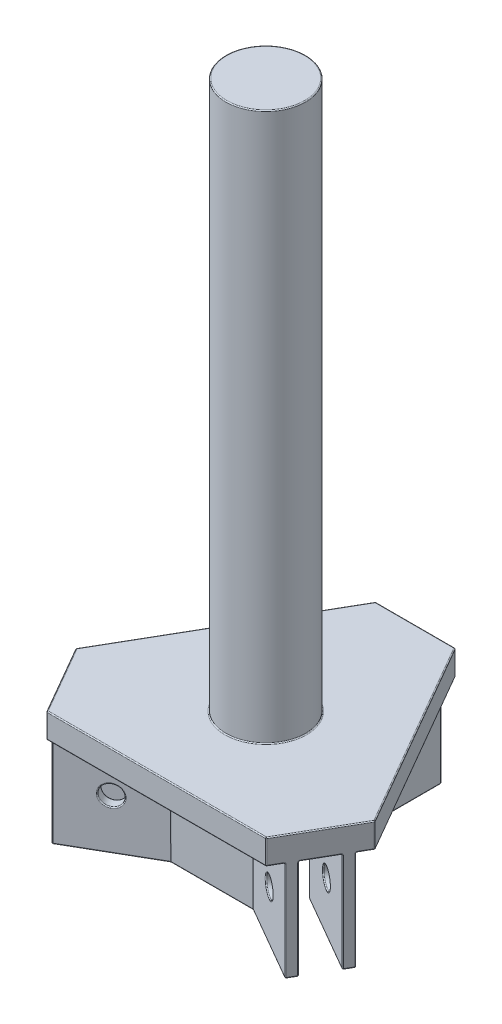
SolidWorks part; units mm, degrees
ref_plane "Front Plane" through (0, 0, 0) normal (0, 0, 1) x (1, 0, 0)
ref_plane "Top Plane" through (0, 0, 0) normal (0, 1, 0) x (1, 0, 0)
ref_plane "Right Plane" through (0, 0, 0) normal (1, 0, 0) x (0, 0, -1)
sketch "Sketch1" plane through (0, 0, 0) normal (0, 1, 0) x (1, 0, 0)
  line L0 (-13, -7.5056) -> (0, 0) construction
  line L1 (0, 0) -> (0, 15.0111) construction
  line L2 (0, 0) -> (13, -7.5056) construction
  line L3 (-4, 15.0111) -> (4, 15.0111)
  line L4 (-15, -4.0415) -> (-11, -10.9697)
  line L5 (15, -4.0415) -> (11, -10.9697)
  line L6 (-4, 15.0111) -> (-15, -4.0415)
  line L7 (-11, -10.9697) -> (11, -10.9697)
  line L8 (15, -4.0415) -> (4, 15.0111)
  point P7 (0, 15.0111)
  point P10 (-13, -7.5056)
  point P13 (13, -7.5056)
  dimension "D1" = 120
  dimension "D2" = 120
  dimension "D3" = 120
  dimension "D4" = 8
  dimension "D5" = 22
extrude "Boss-Extrude1" add sketch "Sketch1" along normal blind 2.5
sketch "Sketch2" plane through (0, 0, 0) normal (0, -1, 0) x (1, 0, 0)
  line L0 (0, 0) -> (-13, 7.5056) construction
  line L1 (-15, 4.0415) -> (-11, 10.9697) construction
  line L2 (13, 7.5056) -> (0, 0) construction
  line L3 (11, 10.9697) -> (15, 4.0415) construction
  line L4 (0, 0) -> (0, -15.0111) construction
  line L5 (4, -15.0111) -> (-4, -15.0111) construction
  line L6 (-12.2, 8.8912) -> (-4.4058, 4.3912)
  line L7 (-4.4058, 4.3912) -> (4.4058, 4.3912)
  line L8 (4.4058, 4.3912) -> (12.2, 8.8912)
  line L9 (-11.7, 9.7572) -> (-4.1378, 5.3912)
  line L10 (-4.1378, 5.3912) -> (4.1378, 5.3912)
  line L11 (4.1378, 5.3912) -> (11.7, 9.7572)
  line L12 (-11.7, 9.7572) -> (-12.2, 8.8912)
  line L13 (11.7, 9.7572) -> (12.2, 8.8912)
  line L14 (2.6, -15.0111) -> (1.6, -15.0111)
  line L15 (1.6, -6.0111) -> (1.6, -15.0111)
  line L16 (6.0058, 1.6199) -> (1.6, -6.0111)
  line L17 (13.8, 6.1199) -> (6.0058, 1.6199)
  line L18 (14.3, 5.2539) -> (13.8, 6.1199)
  line L19 (14.3, 5.2539) -> (6.7378, 0.8879)
  line L20 (6.7378, 0.8879) -> (2.6, -6.2791)
  line L21 (2.6, -6.2791) -> (2.6, -15.0111)
  line L22 (-14.3, 5.2539) -> (-13.8, 6.1199)
  line L23 (-6.0058, 1.6199) -> (-13.8, 6.1199)
  line L24 (-1.6, -6.0111) -> (-6.0058, 1.6199)
  line L25 (-1.6, -15.0111) -> (-1.6, -6.0111)
  line L26 (-2.6, -15.0111) -> (-1.6, -15.0111)
  line L27 (-2.6, -15.0111) -> (-2.6, -6.2791)
  line L28 (-2.6, -6.2791) -> (-6.7378, 0.8879)
  line L29 (-6.7378, 0.8879) -> (-14.3, 5.2539)
  circle A0 centre (0, 0) radius 4 construction
  point P14 (0, 4.3912)
  point P40 (0, 0)
  dimension "D1" = 8
  dimension "D2" = 9
  dimension "D3" = 9
  dimension "D4" = 1.6
  dimension "D5" = 1
  dimension "D6" = 3
extrude "Boss-Extrude2" add sketch "Sketch2" along normal blind 10
sketch "Sketch3" plane through (0, 2.5, 0) normal (0, 1, 0) x (1, 0, 0)
  circle A0 centre (0, 0) radius 4 construction
  circle A1 centre (0, 0) radius 4
extrude "Boss-Extrude3" add sketch "Sketch3" along normal blind 55
sketch "Sketch4" plane through (1.3, 0, 2.2517) normal (0.5, 0, 0.866) x (0.866, 0, -0.5)
  line L0 (-6.2791, -5) -> (-15.0111, -5) construction
  line L1 (-6.2791, -10) -> (-6.2791, 0) construction
  line L2 (-15.0111, -10) -> (-15.0111, 0) construction
  circle A0 centre (-10.6451, -5) radius 1
  dimension "D1" = 2
extrude "Cut-Extrude1" cut sketch "Sketch4" against normal through all
pattern_circular "CirPattern1" count 3 over 360 about axis through (0, 57.5, 0) along (0, -1, 0) of "Cut-Extrude1"
fillet "Fillet1" radius 0.1 104 edges at (-7.5529, -5, 6.2082) (-4.4058, -5, 4.3912) (4.4058, -5, 4.3912) (9.2849, -5, 7.2082) (7.0529, -5, 7.0742) (4.1378, -5, 5.3912) (-4.1378, -5, 5.3912) (-7.0529, -5, 7.0742) (-7.9189, -10, 7.5742) (0, -10, 5.3912) (7.9189, -10, 7.5742) (8.3029, -10, 6.6412) (0, -10, 4.3912) (-8.3029, -10, 6.6412) (9.1529, -5, 3.4369) (6.0058, -5, 1.6199) (1.6, -5, -6.0111) (1.6, -5, -11.6451) (2.6, -5, -9.6451) (2.6, -5, -6.2791) (6.7378, -5, 0.8879) (9.6529, -5, 2.5709) (10.5189, -10, 3.0709) (4.6689, -10, -2.6956) (2.6, -10, -10.6451) (1.6, -10, -10.5111) (3.8029, -10, -2.1956) (9.9029, -10, 3.8699) (-1.6, -5, -9.6451) (-1.6, -5, -6.0111) (-6.0058, -5, 1.6199) (-10.8849, -5, 4.4369) (-9.6529, -5, 2.5709) (-6.7378, -5, 0.8879) (-2.6, -5, -6.2791) (-2.6, -5, -9.6451) (-2.6, -10, -10.6451) (-4.6689, -10, -2.6956) (-10.5189, -10, 3.0709) (-9.9029, -10, 3.8699) (-3.8029, -10, -2.1956) (-1.6, -10, -10.5111) (-15, 1.25, 4.0415) (-11.7, -5, 9.7572) (-11.95, -10, 9.3242) (-12.2, -5, 8.8912) (-13.8, -5, 6.1199) (-14.05, -10, 5.6869) (-14.3, -5, 5.2539) (-11, 1.25, 10.9697) (11, 1.25, 10.9697) (14.3, -5, 5.2539) (14.05, -10, 5.6869) (13.8, -5, 6.1199) (12.2, -5, 8.8912) (11.95, -10, 9.3242) (11.7, -5, 9.7572) (15, 1.25, 4.0415) (4, 1.25, -15.0111) (-4, 1.25, -15.0111) (-2.6, -5, -15.0111) (-2.1, -10, -15.0111) (-1.6, -5, -15.0111) (1.6, -5, -15.0111) (2.1, -10, -15.0111) (2.6, -5, -15.0111) (0, 2.5, -15.0111) (9.5, 2.5, -5.4848) (13, 2.5, 7.5056) (0, 2.5, 10.9697) (-13, 2.5, 7.5056) (-9.5, 2.5, -5.4848) (-11.35, 0, 10.3634) (0, 0, 10.9697) (11.35, 0, 10.3634) (7.9189, 0, 7.5742) (0, 0, 5.3912) (-7.9189, 0, 7.5742) (4.6689, 0, -2.6956) (10.5189, 0, 3.0709) (14.65, 0, 4.6477) (9.5, 0, -5.4848) (3.3, 0, -15.0111) (2.6, 0, -10.6451) (-4.6689, 0, -2.6956) (-2.6, 0, -10.6451) (-3.3, 0, -15.0111) (-9.5, 0, -5.4848) (-14.65, 0, 4.6477) (-10.5189, 0, 3.0709) (-3.8029, 0, -2.1956) (-9.9029, 0, 3.8699) (-13, 0, 7.5056) (-8.3029, 0, 6.6412) (0, 0, 4.3912) (8.3029, 0, 6.6412) (13, 0, 7.5056) (9.9029, 0, 3.8699) (3.8029, 0, -2.1956) (1.6, 0, -10.5111) (0, 0, -15.0111) (-1.6, 0, -10.5111) (0, 2.5, 4) (0, 57.5, 4)
